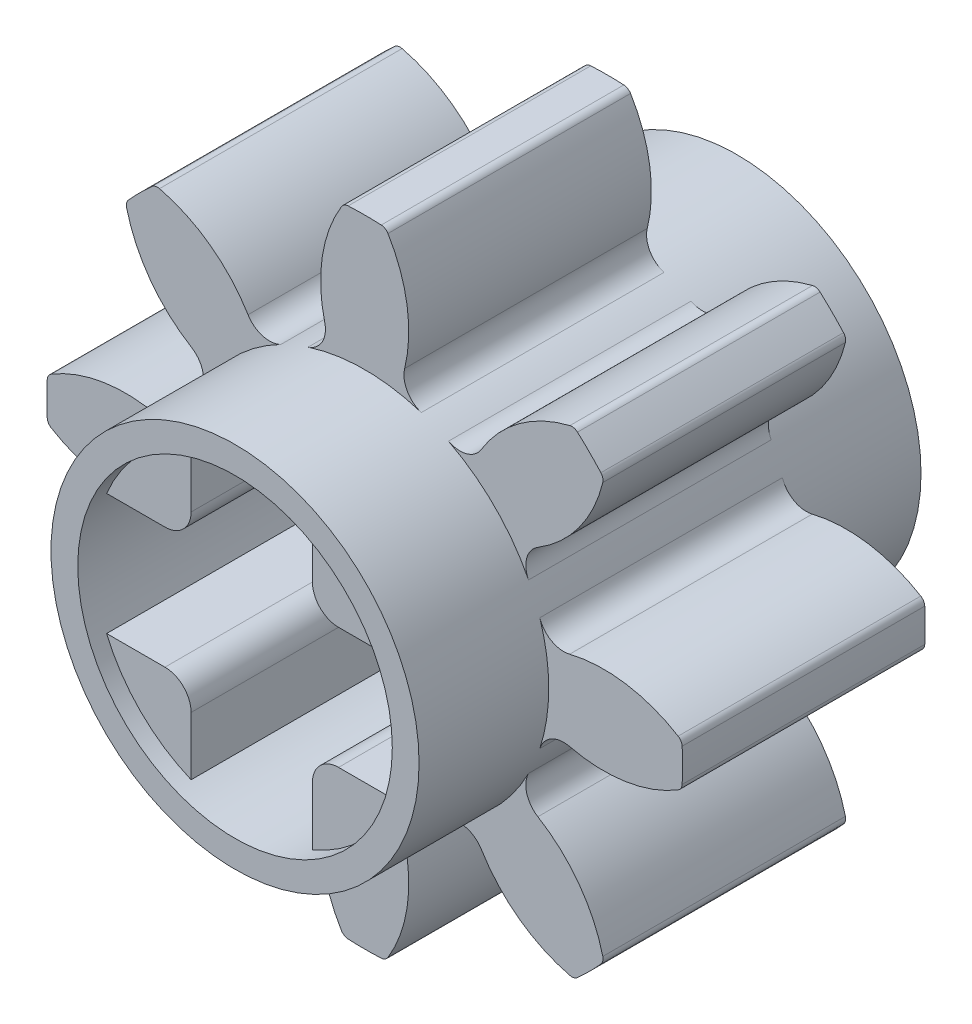
SolidWorks part; units mm, degrees
material "PW40:3:C1:0:1:2:Sc:3:Re:27:"
ref_plane "Front" through (0, 0, 0) normal (0, 0, 1) x (1, 0, 0)
ref_plane "Top" through (0, 0, 0) normal (0, 1, 0) x (1, 0, 0)
ref_plane "Right" through (0, 0, 0) normal (1, 0, 0) x (0, 0, -1)
sketch "Sketch1" plane through (0, 0, 0) normal (0, 0, 1) x (1, 0, 0)
  circle A0 centre (0, 0) radius 2.794
  dimension "D1" = 5.588
extrude "Base-Extrude" add sketch "Sketch1" along normal mid plane 7.62
sketch "Sketch2" plane through (0, 0, 0) normal (0, 0, 1) x (1, 0, 0)
  line L0 (0, 0) -> (0, 3.958) construction
  line L1 (-0.4852, 2.7516) -> (0, 0) construction
  line L2 (0, 0) -> (0.4852, 2.7516) construction
  arc A0 (0.4852, 2.7516) -> (0.3175, 4.8155) centre (-1.5119, 3.6281) ccw
  circle A1 centre (0, 0) radius 2.794 construction
  arc A2 (-0.4852, 2.7516) -> (-0.3175, 4.8155) centre (1.5119, 3.6281) cw
  arc A3 (0.3175, 4.8155) -> (-0.3175, 4.8155) centre (0, 0) ccw
  arc A4 (0.4852, 2.7516) -> (-0.4852, 2.7516) centre (0, 0) ccw
  point P12 (0, 3.8905)
  dimension "D1" = 4.826
  dimension "D2" = 20
  dimension "D3" = 0.635
extrude "Boss-Extrude1" add sketch "Sketch2" along normal mid plane 3.683
fillet "Fillet1" radius 0.127 2 edges at (0.3175, 4.8155, 0) (-0.3175, 4.8155, 0)
fillet "Fillet2" radius 0.381 2 edges at (-0.4852, 2.7516, 0) (0.4852, 2.7516, 0)
pattern_circular "CirPattern2" count 8 every 45 about axis through (0, 0, 0) along (0, 0, 1) of "Boss-Extrude1", "Fillet2", "Fillet1"
sketch "Sketch3" plane through (0, 0, 3.81) normal (0, 0, 1) x (1, 0, 0)
  circle A0 centre (0, 0) radius 2.3876
  dimension "D1" = 4.7752
extrude "Cut-Extrude1" cut sketch "Sketch3" against normal through all
sketch "Sketch5" plane through (0, 0, -3.81) normal (0, 0, -1) x (-1, 0, 0)
  line L0 (0, 0) -> (-4.2828, 0) construction
  line L1 (0, 0) -> (0, -4.2712) construction
  line L2 (-0.9207, -2.2029) -> (-0.9207, -0.9207)
  line L3 (-0.9207, -0.9207) -> (-2.2029, -0.9207)
  circle A0 centre (0, 0) radius 2.3876 construction
  arc A1 (-2.2029, -0.9207) -> (-0.9207, -2.2029) centre (0, 0) ccw
  dimension "D1" = 0.9207
extrude "Boss-Extrude2" add sketch "Sketch5" against normal through all
fillet "Fillet3" radius 0.3969 1 edges at (0.9207, -0.9207, 0)
pattern_circular "CirPattern3" count 4 every 90 about axis through (0, 0, 0) along (0, 0, 1) of "Fillet3", "Boss-Extrude2"
sketch "Sketch6" plane through (0, 0, -3.81) normal (0, 0, -1) x (-1, 0, 0)
  circle A0 centre (0, 0) radius 2.3876
  arc A1 (0.9207, 2.2029) -> (-0.9208, 2.2029) centre (0, 0) ccw construction
extrude "Cut-Extrude2" cut sketch "Sketch6" against normal blind 0.254
sketch "Sketch7" plane through (0, 0, 3.81) normal (0, 0, 1) x (1, 0, 0)
  circle A1 centre (0, 0) radius 2.3876
  circle A2 centre (0, 0) radius 2.3876
  dimension "D1" = 0
extrude "Cut-Extrude3" cut sketch "Sketch7" against normal blind 0.254
